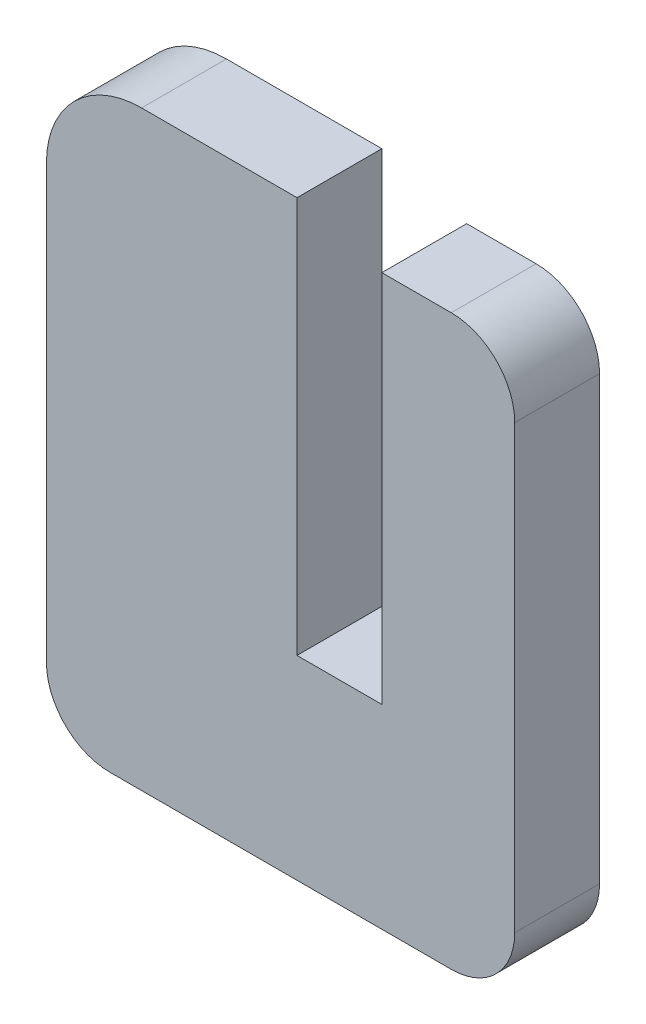
SolidWorks part; units mm, degrees
ref_plane "Front Plane" through (0, 0, 0) normal (0, 0, 1) x (1, 0, 0)
ref_plane "Top Plane" through (0, 0, 0) normal (0, 1, 0) x (1, 0, 0)
ref_plane "Right Plane" through (0, 0, 0) normal (1, 0, 0) x (0, 0, -1)
sketch "Model" plane through (0, 0, 0) normal (0, 0, 1) x (1, 0, 0)
  line L0 (6.385, 35.86) -> (10.765, 35.86)
  line L1 (-10.765, 0) -> (10.765, 0)
  line L2 (-14.765, 4) -> (-14.765, 31.28)
  line L3 (-8.765, 37.28) -> (1.035, 37.28)
  line L4 (14.765, 4) -> (14.765, 31.86)
  line L6 (1.035, 37.28) -> (1.035, 12.28)
  line L7 (1.035, 12.28) -> (6.385, 12.28)
  line L8 (6.385, 35.86) -> (6.385, 12.28)
  arc A0 (-14.765, 4) -> (-10.765, 0) centre (-10.765, 4) ccw
  arc A1 (10.765, 0) -> (14.765, 4) centre (10.765, 4) ccw
  arc A2 (-8.765, 37.28) -> (-14.765, 31.28) centre (-8.765, 31.28) ccw
  arc A3 (14.765, 31.86) -> (10.765, 35.86) centre (10.765, 31.86) ccw
  dimension "D2" = 4
  dimension "D7" = 6
  dimension "D10" = 37.28
  dimension "D12" = 29.53
  dimension "D16" = 25
  dimension "D18" = 15.8
  dimension "D21" = 1.42
  dimension "D3" = 5.35
extrude "Boss-Extrude1" add sketch "Model" along normal blind 5.35
equation "\"mdfthick\"=5.35"
equation "\"D1@Boss-Extrude1\"=\"mdfthick\""
equation "\"D3@Model\"=\"mdfthick\""
